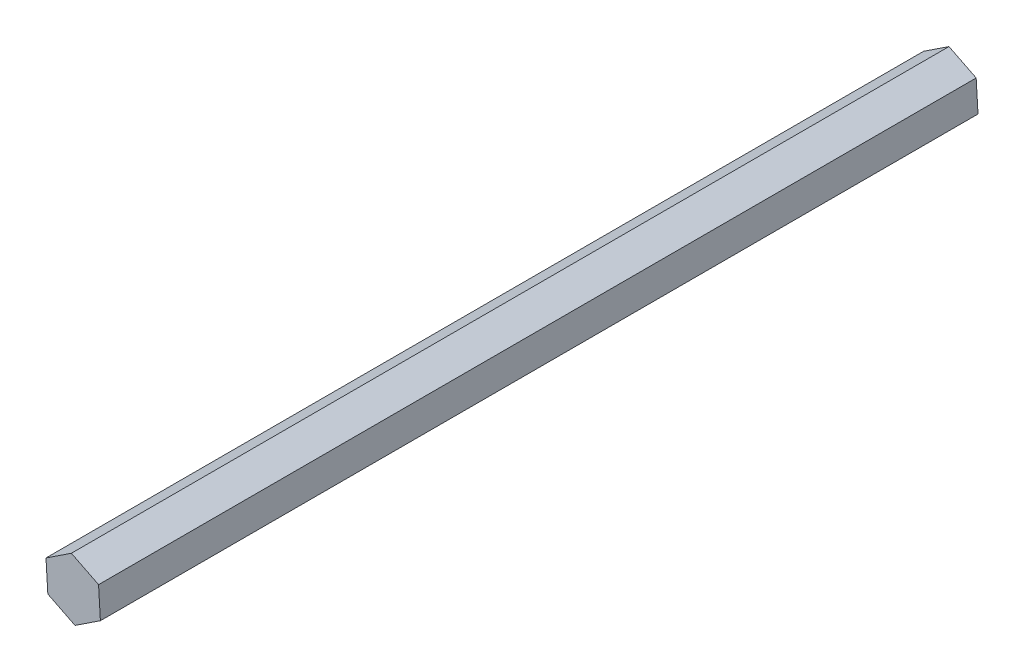
SolidWorks part; units mm, degrees
ref_plane "Front Plane" through (0, 0, 0) normal (0, 0, 1) x (1, 0, 0)
ref_plane "Top Plane" through (0, 0, 0) normal (0, 1, 0) x (1, 0, 0)
ref_plane "Right Plane" through (0, 0, 0) normal (1, 0, 0) x (0, 0, -1)
ref_plane "Plane1" through (0, 0, 0) normal (0, 0, -1) x (-1, 0, 0)
sketch "Sketch1" plane through (0, 0, 0) normal (0, 0, -1) x (-1, 0, 0)
  line L0 (4.9187, 2.4593) -> (0.3295, 5.4894)
  line L1 (0.3295, 5.4894) -> (-4.5892, 3.03)
  line L2 (-4.5892, 3.03) -> (-4.9187, -2.4593)
  line L3 (-4.9187, -2.4593) -> (-0.3295, -5.4894)
  line L4 (-0.3295, -5.4894) -> (4.5892, -3.03)
  line L5 (4.5892, -3.03) -> (4.9187, 2.4593)
extrude "Boss-Extrude1" add sketch "Sketch1" against normal blind 158.75
